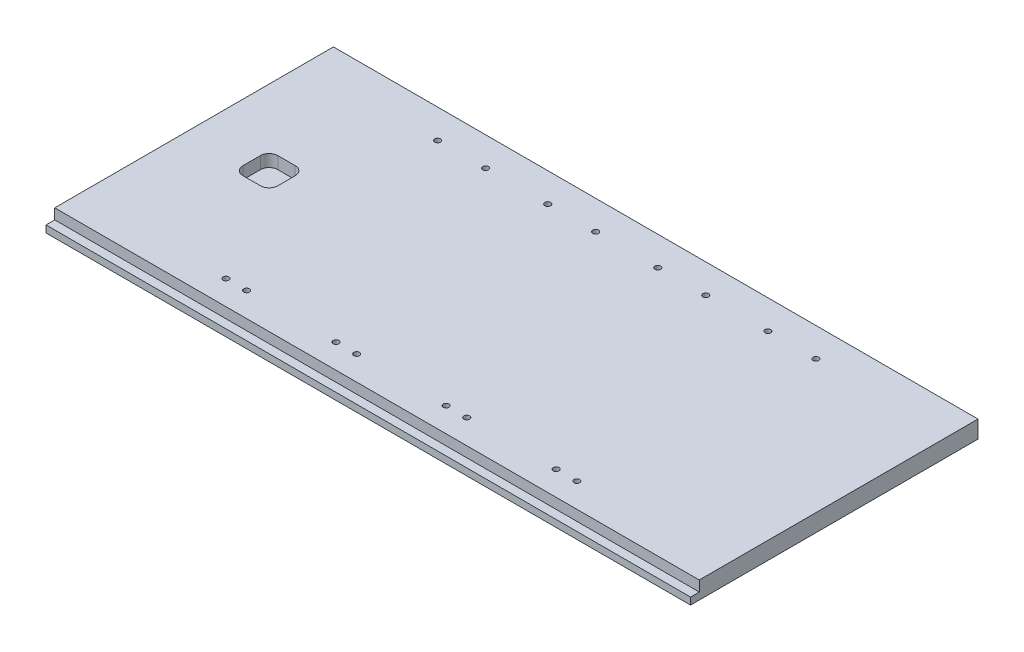
SolidWorks part; units mm, degrees
ref_plane "Front Plane" through (0, 0, 0) normal (0, 0, 1) x (1, 0, 0)
ref_plane "Top Plane" through (0, 0, 0) normal (0, 1, 0) x (1, 0, 0)
ref_plane "Right Plane" through (0, 0, 0) normal (1, 0, 0) x (0, 0, -1)
sketch "Sketch3" plane through (0, 0, 0) normal (0, 1, 0) x (1, 0, 0)
  line L1 (234.95, -104.775) -> (-234.95, -104.775)
  line L2 (234.95, -104.775) -> (234.95, 104.775)
  line L3 (234.95, 104.775) -> (-234.95, 104.775)
  line L4 (-234.95, -104.775) -> (-234.95, 104.775)
  line L5 (234.95, -104.775) -> (-234.95, 104.775) construction
  line L6 (234.95, 104.775) -> (-234.95, -104.775) construction
  point P0 (0, 0)
  dimension "D1" = 469.9
  dimension "D2" = 209.55
extrude "Boss-Extrude1" add sketch "Sketch3" along normal blind 12.7
sketch "Sketch4" plane through (0, 12.7, 0) normal (0, 1, 0) x (1, 0, 0)
  circle A6 centre (-102.9, 83.65) radius 2.1
  circle A8 centre (-22.65, 83.65) radius 2.1
  circle A11 centre (57.6, 83.65) radius 2.1
  circle A13 centre (137.85, 83.65) radius 2.1
  circle A14 centre (112.85, -80.65) radius 2.1
  circle A15 centre (32.6, -80.65) radius 2.1
  circle A16 centre (-47.65, -80.65) radius 2.1
  circle A17 centre (-127.9, -80.65) radius 2.1
  point P0 (-102.9, 83.65)
  point P1 (-22.65, 83.65)
  point P3 (57.6, 83.65)
  point P5 (137.85, 83.65)
  point P7 (-127.9, -80.65)
  point P9 (-47.65, -80.65)
  point P11 (32.6, -80.65)
  point P13 (112.85, -80.65)
  dimension "D1" = 4.2
extrude "Cut-Extrude3" cut sketch "Sketch4" against normal through all
thread "Thread1" pitch 0.8 start angle 0, offset 0, length 0, pitch 0.8, diameter 4.2
ref_plane "Plane3" through (-105, 12.7, -83.65) normal (0, 0, 1) x (-1, 0, 0)
sketch "Thread Profile3" plane through (-105, 12.7, -83.65) normal (0, 0, 1) x (-1, 0, 0)
  line L0 (0, 0) -> (0, 0.8) construction
  line L1 (0, 0) -> (0.433, 0.25)
  line L2 (0.433, 0.25) -> (0.433, 0.35)
  line L3 (0.433, 0.35) -> (0, 0.6)
  line L4 (0.433, 0.3) -> (0, 0.3) construction
  line L11 (0, 0) -> (0, 0.6)
  point P2 (0, 0)
  dimension "Pitch" = 0.8
  dimension "Profile_Angle" = 60
  dimension "Profile_Land" = 0.1
  dimension "Profile_Height" = 0.433
sketch "Sketch5" plane through (0, 12.7, 0) normal (0, 1, 0) x (1, 0, 0)
  circle A0 centre (-137.85, 83.65) radius 2.1
  circle A1 centre (-57.6, 83.65) radius 2.1
  circle A2 centre (22.65, 83.65) radius 2.1
  circle A3 centre (102.9, 83.65) radius 2.1
  circle A4 centre (-112.85, -80.65) radius 2.1
  circle A5 centre (-32.6, -80.65) radius 2.1
  circle A6 centre (47.65, -80.65) radius 2.1
  circle A7 centre (127.9, -80.65) radius 2.1
  point P0 (-137.85, 83.65)
  point P1 (-57.6, 83.65)
  point P3 (22.65, 83.65)
  point P5 (102.9, 83.65)
  point P7 (-112.85, -80.65)
  point P9 (-32.6, -80.65)
  point P11 (47.65, -80.65)
  point P13 (127.9, -80.65)
  dimension "D1" = 4.2
extrude "Cut-Extrude4" cut sketch "Sketch5" against normal through all
sketch "Sketch7" plane through (0, 12.7, 0) normal (0, 1, 0) x (1, 0, 0)
  line L0 (-234.95, -104.775) -> (234.95, -104.775) construction
  line L1 (-192.95, 15.875) -> (-167.55, 15.875)
  line L2 (-192.95, 15.875) -> (-192.95, -9.525)
  line L3 (-192.95, -9.525) -> (-167.55, -9.525)
  line L4 (-167.55, 15.875) -> (-167.55, -9.525)
  line L5 (-192.95, 15.875) -> (-167.55, -9.525) construction
  line L6 (-192.95, -9.525) -> (-167.55, 15.875) construction
  line L8 (-154.85, -86.65) -> (-154.85, 86.65) construction
  point P0 (-180.25, 3.175)
  dimension "D1" = 25.4
  dimension "D2" = 25.4
  dimension "D3" = 107.95
  dimension "D4" = 12.7
extrude "Cut-Extrude5" cut sketch "Sketch7" against normal blind 8.89
sketch "Sketch8" plane through (-234.95, 0, 0) normal (-1, 0, 0) x (0, 0, 1)
  line L1 (104.775, 12.7) -> (98.425, 12.7)
  line L2 (104.775, 12.7) -> (104.775, 5.08)
  line L3 (104.775, 5.08) -> (98.425, 5.08)
  line L4 (98.425, 12.7) -> (98.425, 5.08)
  dimension "D1" = 6.35
  dimension "D2" = 7.62
extrude "Cut-Extrude6" cut sketch "Sketch8" against normal up to next
fillet "Fillet1" radius 6.35 4 edges at (-167.55, 8.255, 9.525) (-192.95, 8.255, 9.525) (-192.95, 8.255, -15.875) (-167.55, 8.255, -15.875)
